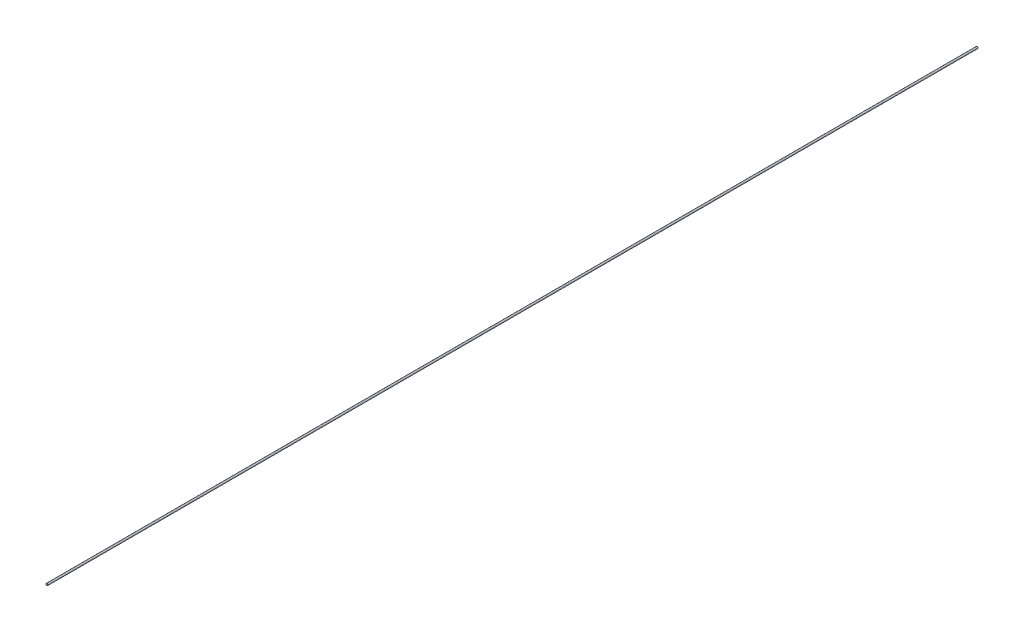
SolidWorks part; units mm, degrees
ref_plane "Front Plane" through (0, 0, 0) normal (0, 0, 1) x (1, 0, 0)
ref_plane "Top Plane" through (0, 0, 0) normal (0, 1, 0) x (1, 0, 0)
ref_plane "Right Plane" through (0, 0, 0) normal (1, 0, 0) x (0, 0, -1)
sketch "Sketch1" plane through (0, 0, 0) normal (0, 0, 1) x (1, 0, 0)
  circle A0 centre (0, 0) radius 0.04
  dimension "D1" = 0.08
extrude "Boss-Extrude1" add sketch "Sketch1" along normal blind 40 contours A0
